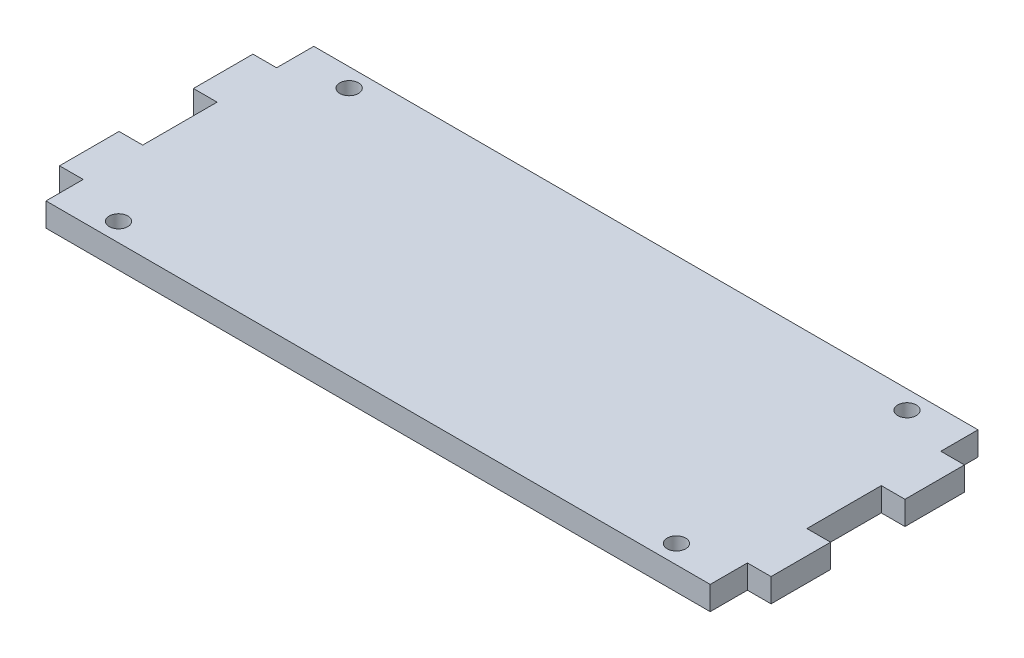
SolidWorks part; units mm, degrees
ref_plane "Front Plane" through (0, 0, 0) normal (0, 0, 1) x (1, 0, 0)
ref_plane "Top Plane" through (0, 0, 0) normal (0, 1, 0) x (1, 0, 0)
ref_plane "Right Plane" through (0, 0, 0) normal (1, 0, 0) x (0, 0, -1)
sketch "Sketch1" plane through (0, 0, 0) normal (0, 1, 0) x (1, 0, 0)
  line L0 (40, -15.5) -> (40, 15.5) construction
  line L1 (37.5, 18) -> (-37.5, 18)
  line L2 (-40, 15.5) -> (-40, -15.5) construction
  line L3 (-37.5, -18) -> (37.5, -18)
  line L4 (34.35, -2.25) -> (34.35, 17.05) construction
  line L5 (34.35, 17.05) -> (-7.65, 17.05) construction
  line L6 (-7.65, 17.05) -> (-7.65, -2.25) construction
  line L7 (-7.65, -2.25) -> (34.35, -2.25) construction
  line L8 (40, 18) -> (40, 15.5) construction
  line L9 (37.5, 18) -> (40, 18)
  line L10 (-40, 15.5) -> (-40, 18) construction
  line L11 (-40, 18) -> (-37.5, 18)
  line L12 (-40, -18) -> (-40, -15.5) construction
  line L13 (-37.5, -18) -> (-40, -18)
  line L14 (40, -18) -> (37.5, -18)
  line L15 (40, -15.5) -> (40, -18) construction
  line L16 (44.5392, 18) -> (44.5392, 13)
  line L17 (-44.7508, 18) -> (-44.7508, 13)
  line L18 (44.5392, 13) -> (47.7192, 13)
  line L19 (-44.7508, 13) -> (-47.9308, 13)
  line L20 (47.7192, 13) -> (47.7192, 5)
  line L21 (47.7192, 5) -> (44.5392, 5)
  line L22 (44.5392, 5) -> (44.5392, -5)
  line L23 (44.5392, -5) -> (47.7192, -5)
  line L24 (47.7192, -5) -> (47.7192, -13)
  line L25 (47.7192, -13) -> (44.5392, -13)
  line L26 (44.5392, -13) -> (44.5392, -18)
  line L27 (47.7192, 13) -> (47.7192, 5)
  line L28 (47.7192, -5) -> (47.7192, -13)
  line L30 (40, 18) -> (44.5392, 18)
  line L32 (44.5392, -18) -> (40, -18)
  line L33 (-40, 18) -> (-44.7508, 18)
  line L34 (-47.9308, 13) -> (-47.9308, 5)
  line L35 (-44.7508, -18) -> (-40, -18)
  line L36 (-47.9308, 5) -> (-44.7508, 5)
  line L37 (-44.7508, 5) -> (-44.7508, -5)
  line L38 (-44.7508, -5) -> (-47.9308, -5)
  line L39 (-47.9308, -5) -> (-47.9308, -13)
  line L40 (-47.9308, -13) -> (-44.7508, -13)
  line L41 (-44.7508, -13) -> (-44.7508, -18)
  line L47 (-40, 18) -> (40, -18) construction
  line L48 (40, 18) -> (-40, -18) construction
  arc A0 (37.5, 18) -> (40, 15.5) centre (37.5, 15.5) ccw construction
  arc A1 (-40, 15.5) -> (-37.5, 18) centre (-37.5, 15.5) ccw construction
  arc A2 (-37.5, -18) -> (-40, -15.5) centre (-37.5, -15.5) ccw construction
  arc A3 (40, -15.5) -> (37.5, -18) centre (37.5, -15.5) ccw construction
  circle A4 centre (-37.5, 15.5) radius 1.25
  circle A5 centre (-37.5, -15.5) radius 1.25
  circle A6 centre (37.5, -15.5) radius 1.25
  circle A7 centre (37.5, 15.5) radius 1.25
extrude "Boss-Extrude1" add sketch "Sketch1" along normal blind 3.18 contours L40 L41 L35 L13 L3 L14 L32 L26 L25 L24 L23 L22 L21 L20 L18 L16 L30 L9 L1 L11 L33 L17 L19 L34 L36 L37 L38 L39 A7 A6 A5 A4
